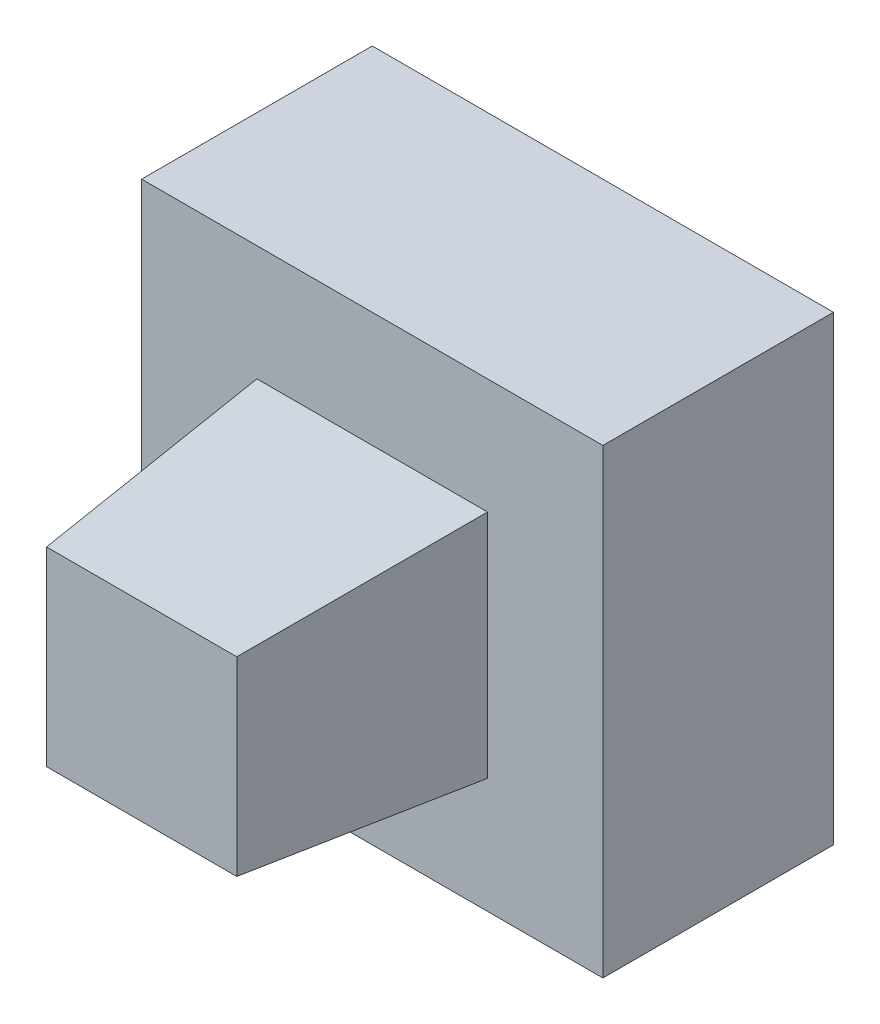
SolidWorks part; units mm, degrees
ref_plane "前视基准面" through (0, 0, 0) normal (0, 0, 1) x (1, 0, 0)
ref_plane "上视基准面" through (0, 0, 0) normal (0, 1, 0) x (1, 0, 0)
ref_plane "右视基准面" through (0, 0, 0) normal (1, 0, 0) x (0, 0, -1)
other "Configuration Table"
sketch "草图1" plane through (0, 0, 0) normal (0, 0, 1) x (1, 0, 0)
  line L1 (0, 0) -> (20, 0)
  line L2 (0, 0) -> (0, 20)
  line L3 (0, 20) -> (20, 20)
  line L4 (20, 0) -> (20, 20)
extrude "BaseBox" add sketch "草图1" along normal blind 10
sketch "草图2" plane through (0, 0, 10) normal (0, 0, 1) x (1, 0, 0)
  line L1 (5, 5) -> (15, 5)
  line L2 (5, 5) -> (5, 15)
  line L3 (5, 15) -> (15, 15)
  line L4 (15, 5) -> (15, 15)
extrude "DraftOutward" add sketch "草图2" along normal blind 10 draft 5
